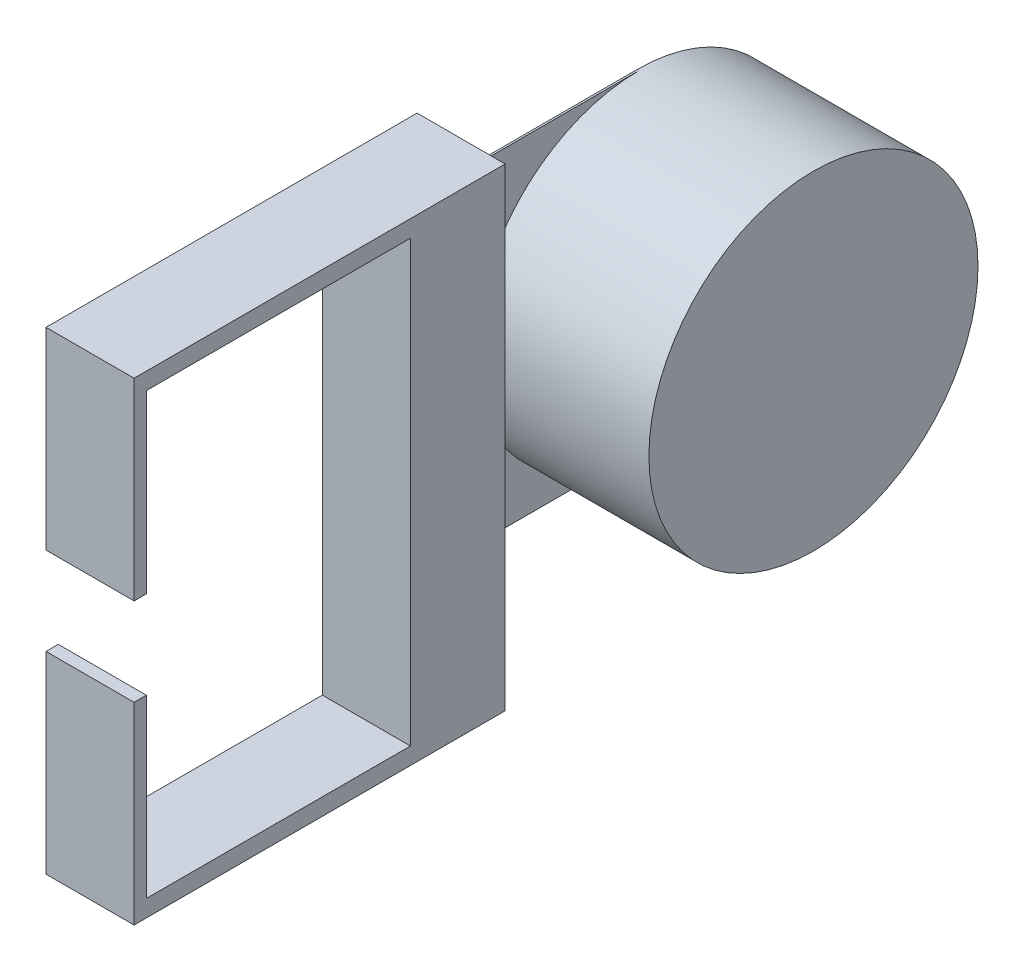
SolidWorks part; units mm, degrees
ref_plane "Front Plane" through (0, 0, 0) normal (1, 0, 0) x (0, 1, 0)
ref_plane "Top Plane" through (0, 0, 0) normal (0, 0, 1) x (0, 1, 0)
ref_plane "Right Plane" through (0, 0, 0) normal (0, 1, 0) x (-1, 0, 0)
sketch "Sketch1" plane through (0, 0, 0) normal (1, 0, 0) x (0, 1, 0)
  circle A0 centre (0, 0) radius 23.7249
  dimension "D1" = 47.4497
extrude "Boss-Extrude1" add sketch "Sketch1" along normal blind 25.4
sketch "Sketch2" plane through (0, 0, 0) normal (0, 0, 1) x (0, 1, 0)
  line L0 (23.7249, -25.4) -> (23.7249, 0) construction
  line L1 (-23.7249, 0) -> (23.7249, 0)
  line L2 (-23.7249, 0) -> (-23.7249, -0.2718)
  line L3 (-23.7249, -0.2718) -> (23.7249, -0.2718)
  line L4 (23.7249, 0) -> (23.7249, -0.2718)
  dimension "D1" = 0.2718
extrude "Boss-Extrude2" add sketch "Sketch2" along normal blind 31.75
sketch "Sketch3" plane through (0, 0, 31.75) normal (0, 0, 1) x (1, 0, 0)
  line L0 (0, 34.1414) -> (0, -34.1414)
  line L1 (0, -34.1414) -> (12.7, -34.1414)
  line L2 (12.7, -34.1414) -> (12.7, 34.1414)
  line L3 (12.7, 34.1414) -> (0, 34.1414)
  line L4 (0, 0) -> (43.309, 0) construction
  dimension "D1" = 12.7
  dimension "D2" = 68.2828
extrude "Boss-Extrude3" add sketch "Sketch3" along normal blind 13.6576
sketch "Sketch4" plane through (0, 0, 45.4076) normal (0, 0, 1) x (1, 0, 0)
  line L0 (12.7, -34.1414) -> (12.7, 34.1414) construction
  line L1 (0, 34.1414) -> (12.7, 34.1414)
  line L2 (0, 34.1414) -> (0, 31.7055)
  line L3 (0, 31.7055) -> (12.7, 31.7055)
  line L4 (12.7, 34.1414) -> (12.7, 31.7055)
  line L6 (0, -34.1414) -> (12.7, -34.1414)
  line L7 (0, -34.1414) -> (0, -31.7055)
  line L8 (0, -31.7055) -> (12.7, -31.7055)
  line L9 (12.7, -34.1414) -> (12.7, -31.7055)
  dimension "D1" = 2.4359
extrude "Boss-Extrude4" add sketch "Sketch4" along normal blind 38.0746
sketch "Sketch5" plane through (0, 0, 83.4822) normal (0, 0, 1) x (1, 0, 0)
  line L0 (12.7, -31.7055) -> (12.7, 31.7055) construction
  line L1 (0, 34.1414) -> (12.7, 34.1414)
  line L2 (0, 34.1414) -> (0, 6.3259)
  line L3 (0, 6.3259) -> (12.7, 6.3259)
  line L4 (12.7, 34.1414) -> (12.7, 6.3259)
  line L6 (0, -34.1414) -> (12.7, -34.1414)
  line L7 (0, -34.1414) -> (0, -6.3259)
  line L8 (0, -6.3259) -> (12.7, -6.3259)
  line L9 (12.7, -34.1414) -> (12.7, -6.3259)
  dimension "D1" = 27.8155
extrude "Boss-Extrude5" add sketch "Sketch5" along normal blind 1.7704
equation "\"deflmax\"= .005"
equation "\"modulus\"= 10000000"
equation "\"Smax\"= 40000"
equation "\"force\"= 800"
equation "\"l1\"= 1"
equation "\"SF\"= 4"
equation "\"d\" = \"SF\" * ( ( \"force\" * \"l1\" * 16 ) / ( \"Smax\" * pi ) ) ^ ( 1 / 3 )"
equation "\"t2\"= \"force\" / ( \"d\" * \"Smax\" )"
equation "\"l2\"= \"modulus\" * \"d\" * \"t2\" * \"deflmax\" / \"force\""
equation "\"t4\" = .5"
equation "\"l4\"= 1.499"
equation "\"w4\" = \"l4\" * \"force\" * \"SF\" / 2 / ( \"modulus\" * \"deflmax\" * \"t4\" )"
equation "\"l5\"= \"w4\" + .9992"
equation "\"w5\" = ( ( \"force\" * \"w4\" ^ 3 * 3 ) / ( \"modulus\" * \"t4\" * \"deflmax\" * 4 ) ) ^ ( 1 / 3 )"
equation "\"l3\"= .498 + 2 * .9992 + ( \"w4\" * 2 )"
equation "\"w3\"= ( ( \"force\" * \"l3\" ^ 3 ) / ( \"modulus\" * \"t4\" * \"deflmax\" * 4 ) ) ^ ( 1 / 3 )"
equation "\"a\"= .498"
equation "\"b\"= .9992"
